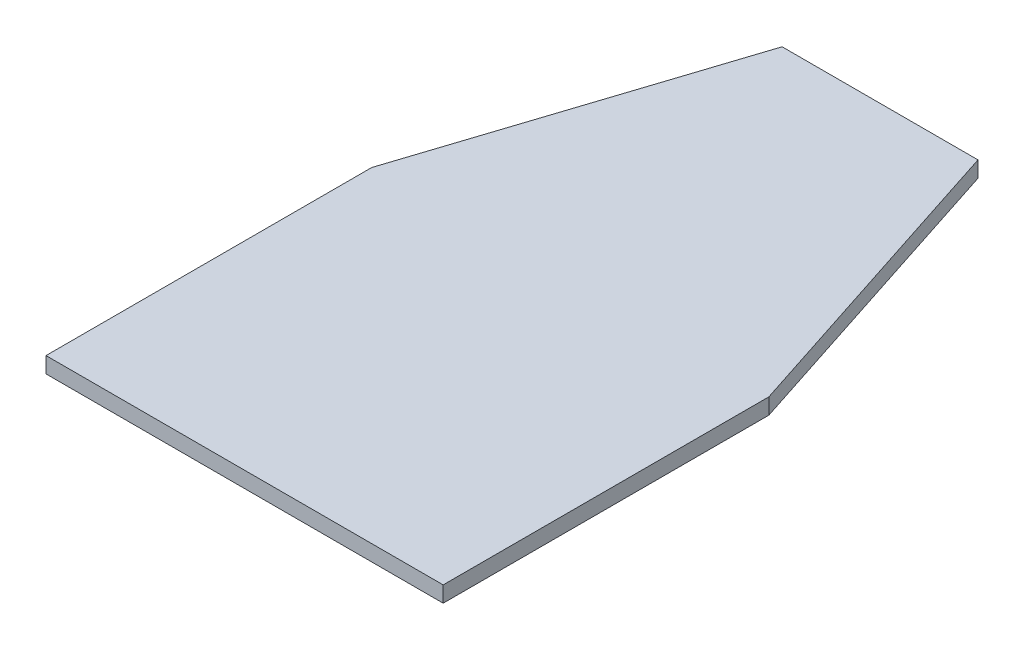
SolidWorks part; units mm, degrees
ref_plane "Plano frontal" through (0, 0, 0) normal (0, 0, 1) x (1, 0, 0)
ref_plane "Plano superior" through (0, 0, 0) normal (0, 1, 0) x (1, 0, 0)
ref_plane "Plano direito" through (0, 0, 0) normal (1, 0, 0) x (0, 0, -1)
sketch "Esboço2" plane through (0, 0, 0) normal (0, 1, 0) x (1, 0, 0)
  line L0 (-125, 0) -> (125, 0)
  line L1 (125, 0) -> (125, 205.0171)
  line L2 (125, 205.0171) -> (61.6462, 400)
  line L3 (61.6462, 400) -> (-61.6462, 400)
  line L4 (-61.6462, 400) -> (-125, 205.0171)
  line L5 (-125, 205.0171) -> (-125, 0)
  point P3 (0, 400)
  dimension "D1" = 250
  dimension "D2" = 400
  dimension "D3" = 72
extrude "Ressalto-extrusão1" add sketch "Esboço2" along normal blind 10
